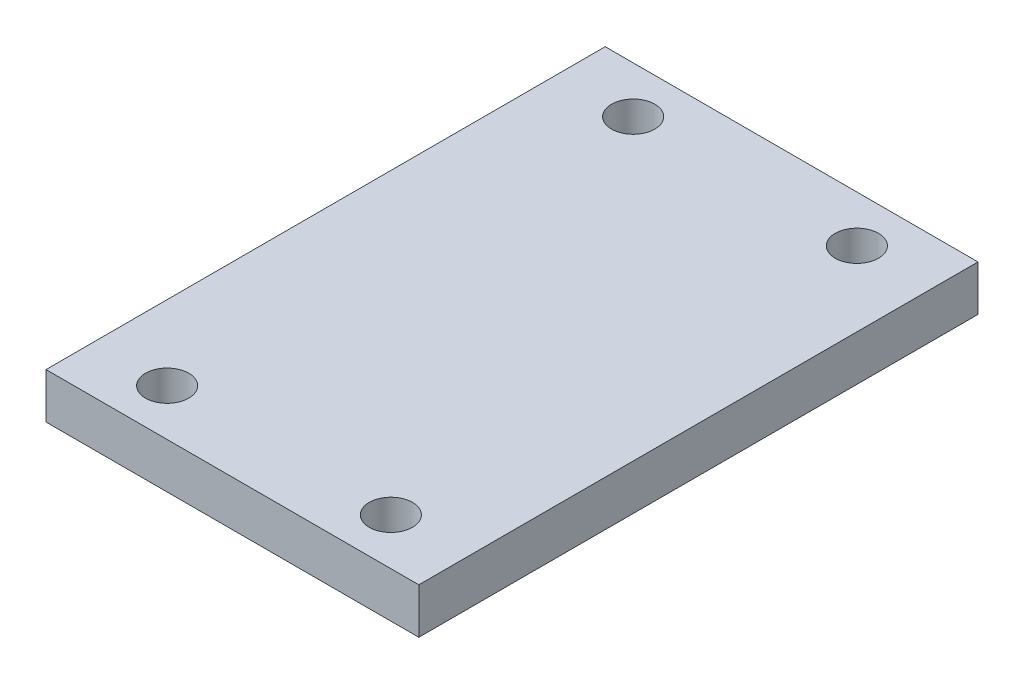
SolidWorks part; units mm, degrees
ref_plane "Front Plane" through (0, 0, 0) normal (0, 0, 1) x (1, 0, 0)
ref_plane "Top Plane" through (0, 0, 0) normal (0, 1, 0) x (1, 0, 0)
ref_plane "Right Plane" through (0, 0, 0) normal (1, 0, 0) x (0, 0, -1)
sketch "Sketch1" plane through (0, 0, 0) normal (0, 1, 0) x (1, 0, 0)
  line L0 (0, 19.05) -> (0, -19.05)
  line L1 (-25.4, 19.05) -> (0, 19.05)
  line L2 (-25.4, 19.05) -> (-25.4, -19.05)
  line L3 (-25.4, -19.05) -> (0, -19.05)
  line L4 (-12.7, 19.05) -> (-12.7, -19.05) construction
  line L5 (-25.4, 0) -> (0, 0) construction
  circle A0 centre (-5.08, 15.875) radius 1.4732
  circle A1 centre (-20.32, -15.875) radius 1.4732
  circle A2 centre (-20.32, 15.875) radius 1.4732
  circle A3 centre (-5.08, -15.875) radius 1.4732
  point P0 (0, 0)
  dimension "D2" = 25.4
  dimension "D4" = 15.875
  dimension "D5" = 2.9464
  dimension "D1" = 7.62
  dimension "D6" = 38.1
extrude "Boss-Extrude1" add sketch "Sketch1" along normal blind 3.0988
sketch "Sketch3" plane through (0, 0, 0) normal (0, -1, 0) x (1, 0, 0)
  line L0 (0, 0) -> (-25.4, 0) construction
  line L1 (-25.4, -19.05) -> (-25.4, 19.05) construction
